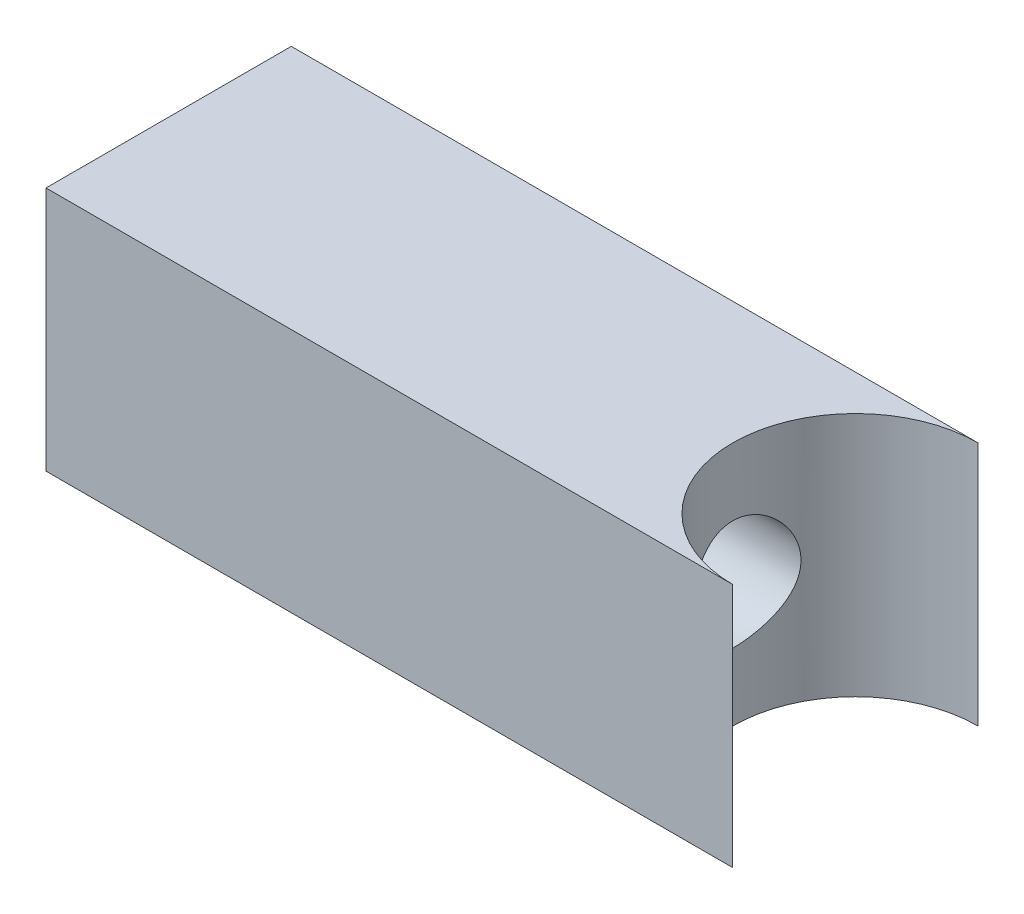
SolidWorks part; units mm, degrees
ref_plane "Front Plane" through (0, 0, 0) normal (0, 0, 1) x (1, 0, 0)
ref_plane "Top Plane" through (0, 0, 0) normal (0, 1, 0) x (1, 0, 0)
ref_plane "Right Plane" through (0, 0, 0) normal (1, 0, 0) x (0, 0, -1)
sketch "Sketch1" plane through (0, 0, 0) normal (0, 1, 0) x (1, 0, 0)
  line L1 (38.1, -25.4) -> (-38.1, -25.4)
  line L2 (38.1, -25.4) -> (38.1, 25.4)
  line L3 (38.1, 25.4) -> (-38.1, 25.4)
  line L4 (-38.1, -25.4) -> (-38.1, 25.4)
  line L5 (38.1, -25.4) -> (-38.1, 25.4) construction
  line L6 (38.1, 25.4) -> (-38.1, -25.4) construction
  point P0 (0, 0)
  dimension "D1" = 76.2
  dimension "D2" = 50.8
sketch "Sketch10" plane through (0, 0, 0) normal (1, 0, 0) x (0, 0, -1)
  line L0 (-12.7, 0) -> (0, 0) construction
  line L1 (0, 0) -> (0, -12.7) construction
  line L2 (0, 0) -> (0, 12.7) construction
  line L3 (0, 0) -> (12.7, 0) construction
  line L4 (6.35, 10.16) -> (-6.35, 10.16)
  line L5 (-6.5427, 9.7405) -> (-2.54, 5.08)
  line L6 (6.5427, 9.7405) -> (2.54, 5.08)
  line L7 (2.54, 5.08) -> (-2.54, 5.08)
  line L8 (-5.08, -2.54) -> (-5.08, 2.54)
  line L9 (-5.08, 2.54) -> (-9.7405, 6.5427)
  line L10 (-10.16, -6.35) -> (-10.16, 6.35)
  line L11 (-9.7405, -6.5427) -> (-5.08, -2.54)
  line L12 (-12.7, -2.54) -> (-12.7, 2.54)
  line L13 (-12.7, 2.54) -> (-10.16, 2.54)
  line L14 (-10.16, 2.54) -> (-10.16, -2.54)
  line L15 (-10.16, -2.54) -> (-12.7, -2.54)
  line L16 (2.54, 12.7) -> (-2.54, 12.7)
  line L17 (-2.54, 12.7) -> (-2.54, 10.16)
  line L18 (-2.54, 10.16) -> (2.54, 10.16)
  line L19 (2.54, 10.16) -> (2.54, 12.7)
  line L20 (2.54, -12.7) -> (-2.54, -12.7)
  line L21 (2.54, -5.08) -> (-2.54, -5.08)
  line L23 (6.35, -10.16) -> (-6.35, -10.16)
  line L24 (-2.54, -12.7) -> (-2.54, -10.16)
  line L26 (2.54, -12.7) -> (2.54, -10.16)
  line L27 (-2.54, -10.16) -> (2.54, -10.16)
  line L28 (-2.54, -5.08) -> (-6.5427, -9.7405)
  line L29 (2.54, -5.08) -> (6.5427, -9.7405)
  line L30 (5.08, -2.54) -> (5.08, 2.54)
  line L31 (12.7, -2.54) -> (12.7, 2.54)
  line L32 (12.7, 2.54) -> (10.16, 2.54)
  line L33 (10.16, 2.54) -> (10.16, -2.54)
  line L34 (10.16, -2.54) -> (12.7, -2.54)
  line L35 (10.16, -6.35) -> (10.16, 6.35)
  line L36 (5.08, 2.54) -> (9.7405, 6.5427)
  line L37 (5.08, -2.54) -> (9.7405, -6.5427)
  line L39 (12.7, -12.7) -> (-12.7, -12.7)
  line L40 (12.7, -12.7) -> (12.7, 12.7)
  line L41 (12.7, 12.7) -> (-12.7, 12.7)
  line L42 (-12.7, -12.7) -> (-12.7, 12.7)
  line L43 (12.7, -12.7) -> (-12.7, 12.7) construction
  line L44 (12.7, 12.7) -> (-12.7, -12.7) construction
  line L45 (15.875, -15.875) -> (-15.875, -15.875)
  line L46 (15.875, -15.875) -> (15.875, 15.875)
  line L47 (15.875, 15.875) -> (-15.875, 15.875)
  line L48 (-15.875, -15.875) -> (-15.875, 15.875)
  line L49 (15.875, -15.875) -> (-15.875, 15.875) construction
  line L50 (15.875, 15.875) -> (-15.875, -15.875) construction
  arc A0 (-10.16, -6.35) -> (-9.7405, -6.5427) centre (-9.906, -6.35) ccw
  arc A1 (-9.7405, 6.5427) -> (-10.16, 6.35) centre (-9.906, 6.35) ccw
  arc A2 (6.35, 10.16) -> (6.5427, 9.7405) centre (6.35, 9.906) cw
  arc A3 (-6.35, 10.16) -> (-6.5427, 9.7405) centre (-6.35, 9.906) ccw
  arc A4 (-6.35, -10.16) -> (-6.5427, -9.7405) centre (-6.35, -9.906) cw
  arc A6 (6.5427, -9.7405) -> (6.35, -10.16) centre (6.35, -9.906) cw
  arc A8 (9.7405, -6.5427) -> (10.16, -6.35) centre (9.906, -6.35) ccw
  arc A9 (10.16, 6.35) -> (9.7405, 6.5427) centre (9.906, 6.35) ccw
  point P4 (0, 5.08)
  point P10 (0, 10.16)
  point P17 (-5.08, 0)
  point P20 (-10.16, 0)
  point P30 (-12.7, 0)
  point P35 (0, 12.7)
  point P39 (0, -12.7)
  point P42 (0, -5.08)
  point P46 (0, -10.16)
  point P52 (5.08, 0)
  point P55 (12.7, 0)
  point P60 (10.16, 0)
  dimension "D1" = 0.254
  dimension "D16" = 0.254
  dimension "D17" = 31.75
  dimension "D2" = 5.08
  dimension "D3" = 5.08
  dimension "D4" = 2.54
  dimension "D5" = 2.54
  dimension "D6" = 5.08
  dimension "D7" = 12.7
  dimension "D8" = 5.08
  dimension "D9" = 12.7
  dimension "D10" = 5.08
  dimension "D11" = 5.08
  dimension "D12" = 12.7
  dimension "D13" = 5.08
  dimension "D14" = 5.08
  dimension "D15" = 2.54
extrude "Boss-Extrude3" add sketch "Sketch10" against normal blind 12.7 separate body
sketch "Sketch11" plane through (0, 0, 0) normal (1, 0, 0) x (0, 0, -1)
  line L1 (15.875, -15.875) -> (-15.875, -15.875)
  line L2 (15.875, -15.875) -> (15.875, 15.875)
  line L3 (15.875, 15.875) -> (-15.875, 15.875)
  line L4 (-15.875, -15.875) -> (-15.875, 15.875)
  line L5 (15.875, -15.875) -> (-15.875, 15.875) construction
  line L6 (15.875, 15.875) -> (-15.875, -15.875) construction
  point P0 (0, 0)
extrude "Boss-Extrude4" add sketch "Sketch11" along normal blind 76.2
hole_wizard "CBORE for 1/4 Binding Head Machine Screw1" positions "Sketch12" profile "Sketch14" counterbore size "1/4" standard "ANSI Inch" end condition through all
sketch "Sketch12" plane through (76.2, 0, 0) normal (1, 0, 0) x (0, 0, -1)
  point P0 (0, 0)
sketch "Sketch14" plane through (76.2, 0, 0) normal (0, 1, 0) x (0, 0, -1)
  line L0 (0, 0) -> (0, 88.9)
  line L1 (0, 88.9) -> (3.3782, 88.9)
  line L3 (3.3782, 88.9) -> (3.3782, 69.85)
  line L4 (3.3782, 69.85) -> (7.1437, 69.85)
  line L5 (7.1437, 69.85) -> (7.1437, 0)
  line L7 (7.1437, 0) -> (0, 0)
  line L11 (0, -6.35) -> (0, 107.95) construction
  dimension "Thru Hole Dia." = 6.7564
  dimension "Thru Hole Depth" = 88.9
  dimension "C'Bore Dia." = 14.2875
  dimension "C'Bore Depth" = 69.85
sketch "Sketch15" plane through (0, 15.875, 0) normal (0, 1, 0) x (1, 0, 0)
  line L0 (-12.7, 0) -> (76.2, 0) construction
  line L1 (-12.7, 15.875) -> (-12.7, -15.875) construction
  line L2 (76.2, 15.875) -> (76.2, -15.875) construction
  line L3 (76.2, 15.875) -> (76.2, -15.875)
  arc A0 (76.2, -15.875) -> (76.2, 15.875) centre (76.2, 0) cw
extrude "Cut-Extrude1" cut sketch "Sketch15" against normal up to surface (31.75 mm away) up to face at (31.75, -15.875, 0)
